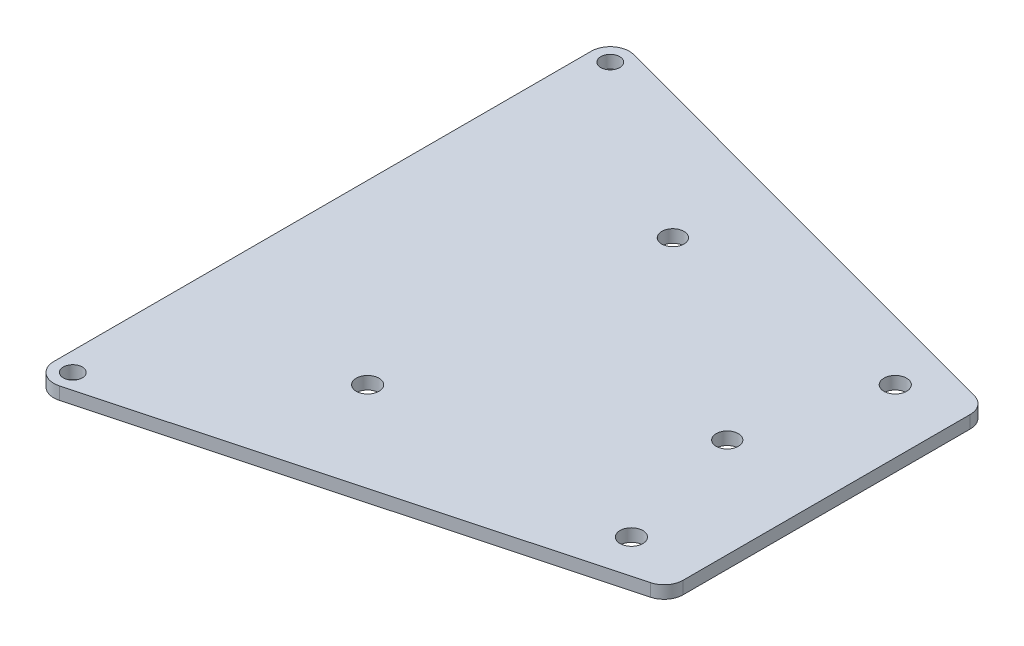
SolidWorks part; units mm, degrees
ref_plane "Front Plane" through (0, 0, 0) normal (0, 0, 1) x (1, 0, 0)
ref_plane "Top Plane" through (0, 0, 0) normal (0, 1, 0) x (1, 0, 0)
ref_plane "Right Plane" through (0, 0, 0) normal (1, 0, 0) x (0, 0, -1)
sketch "Croquis1" plane through (0, 0, 0) normal (0, 1, 0) x (1, 0, 0)
  line L0 (0, 0) -> (0, -85) construction
  line L1 (0.7782, 2.8973) -> (74.4982, -16.9032)
  line L2 (76.72, -19.8006) -> (76.72, -65.1994)
  line L3 (74.4982, -68.0968) -> (0.7782, -87.8973)
  line L4 (-3, -85) -> (-3, 0)
  circle A0 centre (25, -21.65) radius 1.8
  circle A1 centre (25, -63.37) radius 1.8
  circle A2 centre (66.72, -21.65) radius 1.8
  circle A3 centre (66.72, -63.37) radius 1.8
  circle A4 centre (0, 0) radius 1.5
  circle A5 centre (0, -85) radius 1.5
  circle A6 centre (49, -26.465) radius 1.5
  circle A7 centre (49, -58.535) radius 1.5
  arc A8 (0.7782, -87.8973) -> (-3, -85) centre (0, -85) cw
  arc A9 (-3, 0) -> (0.7782, 2.8973) centre (0, 0) cw
  arc A10 (76.72, -65.1994) -> (74.4982, -68.0968) centre (73.72, -65.1994) cw
  arc A11 (74.4982, -16.9032) -> (76.72, -19.8006) centre (73.72, -19.8006) cw
  circle A12 centre (29, -65.9) radius 1.75
  circle A13 centre (29, -19.1) radius 1.75
  circle A14 centre (61, -42.5) radius 1.75
  point P17 (0, -42.5)
  point P24 (76.72, -42.5)
  point P27 (0, 0)
  point P30 (0, 0)
  point P31 (0, 0)
  point P32 (0, 0)
  point P33 (-3, -42.5)
  point P36 (76.72, -67.5)
  point P39 (76.72, -17.5)
  point P42 (0, 0)
  point P43 (0, 0)
  dimension "D3" = 3.6
  dimension "D4" = 3
  dimension "D11" = 3
  dimension "D14" = 3
  dimension "D16" = 3.5
  dimension "D1" = 41.72
  dimension "D2" = 41.72
  dimension "D5" = 85
  dimension "D6" = 49
  dimension "D7" = 32.07
  dimension "D8" = 16.035
  dimension "D9" = 20.85
  dimension "D10" = 25
  dimension "D12" = 50
  dimension "D13" = 10
  dimension "D15" = 46.8
  dimension "D17" = 23.4
  dimension "D18" = 32
  dimension "D19" = 32
extrude "Saliente-Extruir1" add sketch "Croquis1" along normal blind 2
equation "\"D8@Croquis1\"=32.07/2"
equation "\"D17@Croquis1\"=\"D15@Croquis1\"/2"
